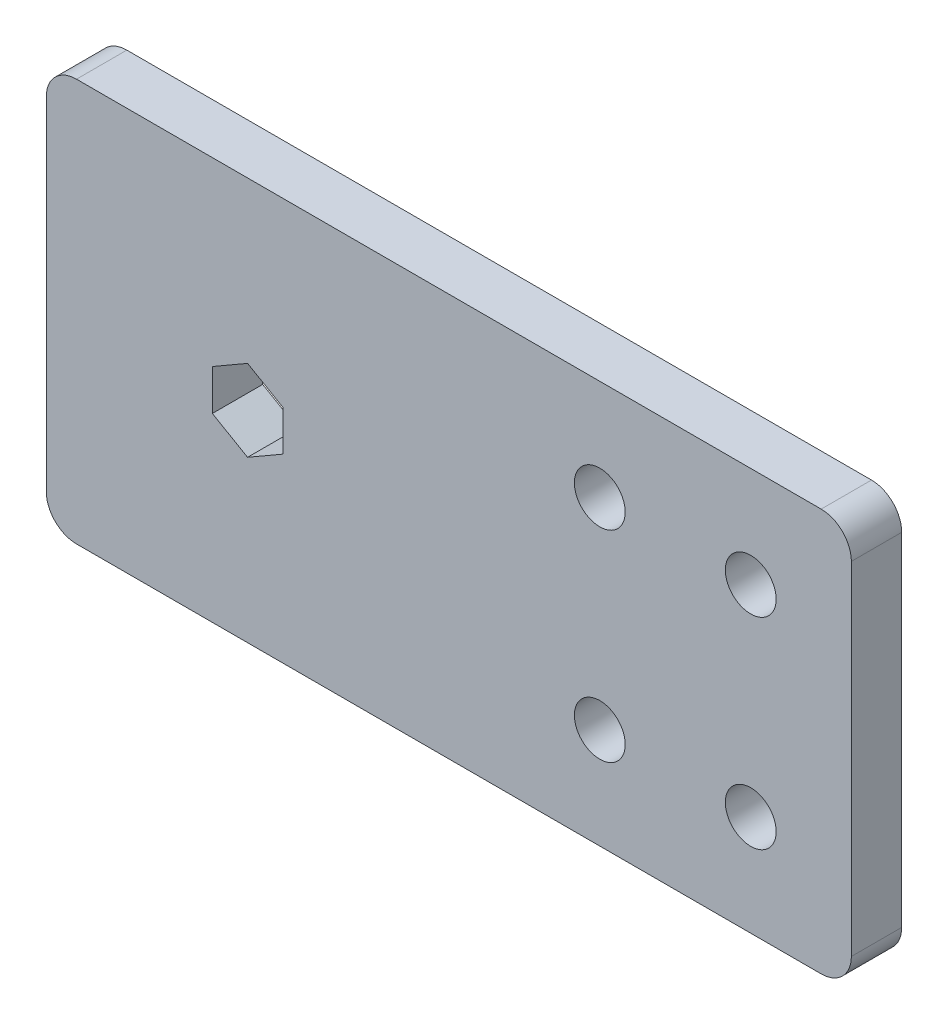
SolidWorks part; units mm, degrees
ref_plane "Front Plane" through (0, 0, 0) normal (0, 0, 1) x (1, 0, 0)
ref_plane "Top Plane" through (0, 0, 0) normal (0, 1, 0) x (1, 0, 0)
ref_plane "Right Plane" through (0, 0, 0) normal (1, 0, 0) x (0, 0, -1)
sketch "Sketch1" plane through (0, 0, 0) normal (0, 0, 1) x (1, 0, 0)
  line L1 (20, 40) -> (80, 40)
  line L2 (80, 40) -> (80, 0)
  line L3 (80, 0) -> (20, 0)
  line L4 (20, 40) -> (0, 40)
  line L5 (0, 40) -> (0, 20)
  line L6 (0, 20) -> (0, 0)
  line L7 (0, 0) -> (20, 0)
  dimension "D1" = 20
extrude "Boss-Extrude1" add sketch "Sketch1" along normal blind 5
sketch "Sketch2" plane through (0, 0, 5) normal (0, 0, 1) x (1, 0, 0)
  line L0 (80, 40) -> (0, 40) construction
  line L1 (80, 0) -> (80, 40) construction
  line L15 (20, 15.9585) -> (23.5, 17.9793)
  line L16 (23.5, 17.9793) -> (23.5, 22.0207)
  line L17 (23.5, 22.0207) -> (20, 24.0415)
  line L18 (20, 24.0415) -> (16.5, 22.0207)
  line L19 (16.5, 22.0207) -> (16.5, 17.9793)
  line L20 (16.5, 17.9793) -> (20, 15.9585)
  circle A1 centre (20, 20) radius 3.5 construction
  dimension "D1" = 20
  dimension "D2" = 60
  dimension "D4" = 7
extrude "Cut-Extrude1" cut sketch "Sketch2" against normal up to next
sketch "Sketch3" plane through (0, 0, 5) normal (0, 0, 1) x (1, 0, 0)
  line L0 (80, 0) -> (80, 40) construction
  line L1 (80, 40) -> (0, 40) construction
  line L2 (0, 0) -> (80, 0) construction
  circle A0 centre (55, 30) radius 2.525
  circle A1 centre (55, 10) radius 2.525
  circle A2 centre (70, 30) radius 2.525
  circle A3 centre (70, 10) radius 2.525
  dimension "D1" = 5.05
  dimension "D2" = 5.05
  dimension "D3" = 5.05
  dimension "D4" = 5.05
  dimension "D5" = 10
  dimension "D6" = 10
  dimension "D7" = 10
  dimension "D8" = 15
  dimension "D9" = 10
  dimension "D10" = 10
  dimension "D11" = 10
  dimension "D12" = 15
extrude "Cut-Extrude2" cut sketch "Sketch3" against normal up to next
fillet "Fillet1" radius 3 2 edges at (80, 0, 2.5) (80, 40, 2.5)
fillet "Fillet2" radius 3 2 edges at (0, 0, 2.5) (0, 40, 2.5)
